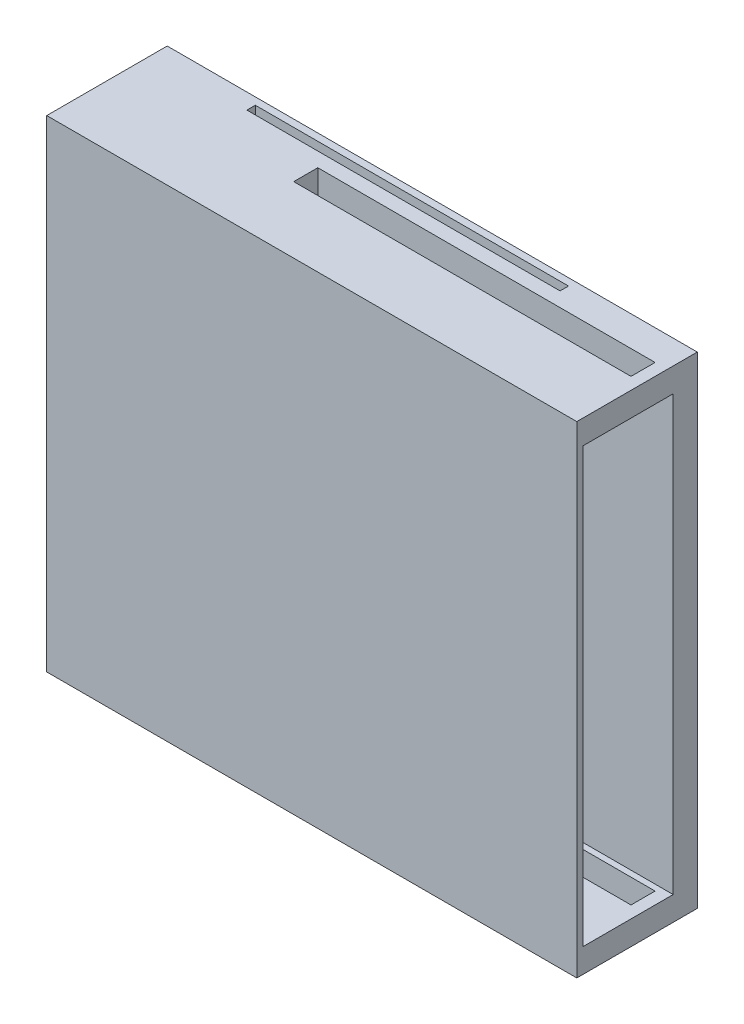
SolidWorks part; units mm, degrees
ref_plane "Front Plane" through (0, 0, 0) normal (0, 0, 1) x (1, 0, 0)
ref_plane "Top Plane" through (0, 0, 0) normal (0, 1, 0) x (1, 0, 0)
ref_plane "Right Plane" through (0, 0, 0) normal (1, 0, 0) x (0, 0, -1)
sketch "Sketch1" plane through (0, 0, 0) normal (0, 1, 0) x (1, 0, 0)
  line L0 (-220, -50) -> (-220, 14.996) construction
  line L1 (-220, 50) -> (220, 50)
  line L2 (-220, 50) -> (-220, -50)
  line L3 (-220, -50) -> (220, -50)
  line L4 (220, 50) -> (220, -50)
  line L5 (-220, 50) -> (220, -50) construction
  line L6 (-220, -50) -> (220, 50) construction
  line L7 (-220, 14.996) -> (70, 14.996) construction
  line L8 (-220, 40.5) -> (-10.877, 40.5) construction
  line L9 (-70, 24.996) -> (210, 24.996)
  line L10 (-70, 24.996) -> (-70, 4.996)
  line L11 (-70, 4.996) -> (210, 4.996)
  line L12 (210, 24.996) -> (210, 4.996)
  line L13 (-70, 24.996) -> (210, 4.996) construction
  line L14 (-70, 4.996) -> (210, 24.996) construction
  line L15 (-10.877, 40.5) -> (-10.877, 50) construction
  line L16 (70, -50) -> (70, 14.996) construction
  line L17 (-140.877, 44) -> (119.123, 44)
  line L18 (-140.877, 44) -> (-140.877, 37)
  line L19 (-140.877, 37) -> (119.123, 37)
  line L20 (119.123, 44) -> (119.123, 37)
  line L21 (-140.877, 44) -> (119.123, 37) construction
  line L22 (-140.877, 37) -> (119.123, 44) construction
  line L23 (119.123, 40.5) -> (220, 40.5) construction
  point P0 (0, 0)
extrude "Boss-Extrude1" add sketch "Sketch1" along normal blind 20
ref_plane "Plane3" through (0, 0, 50) normal (0, 0, 1) x (1, 0, 0)
sketch "Sketch7" plane through (0, 0, 50) normal (0, 0, 1) x (1, 0, 0)
  line L0 (17.6108, 0) -> (17.6108, -380) construction
  line L1 (-220, 0) -> (220, 0) construction
sketch "Sketch8" plane through (0, 0, 0) normal (0, -1, 0) x (1, 0, 0)
  line L0 (-220, 50) -> (-220, 45)
  line L1 (-220, 50) -> (220, 50)
  line L2 (-220, 45) -> (220, 45)
  line L3 (220, 50) -> (220, 45)
  line L4 (-220, -50) -> (-220, 50) construction
extrude "Boss-Extrude2" add sketch "Sketch8" along normal blind 360
pattern_linear "LPattern2" count 2 spacing 380 along (0, -1, 0) of "Boss-Extrude1"
sketch "Sketch10" plane through (0, 0, 0) normal (0, -1, 0) x (1, 0, 0)
  line L0 (220, -50) -> (-220, -50)
  line L1 (220, -50) -> (220, -30)
  line L2 (-220, -50) -> (-220, -30)
  line L3 (220, -30) -> (-220, -30)
extrude "Boss-Extrude3" add sketch "Sketch10" along normal up to surface (360 mm away) up to face at (-55, -360, -2.5)
sketch "Sketch11" plane through (0, 0, -37) normal (0, 0, -1) x (-1, 0, 0)
  line L0 (140.877, 20) -> (140.877, 0) construction
  line L1 (140.877, 20) -> (140.877, 11.5) construction
  line L2 (140.877, 11.5) -> (140.877, 8.5)
  line L3 (140.877, 11.5) -> (-119.1208, 11.5)
  line L4 (140.877, 8.5) -> (-119.1208, 8.5)
  line L5 (-119.1208, 11.5) -> (-119.1208, 8.5)
extrude "Cut-Extrude1" cut sketch "Sketch11" against normal blind 1.5
sketch "Sketch16" plane through (0, 0, -44) normal (0, 0, 1) x (1, 0, 0)
  line L0 (-140.877, 20) -> (-140.877, 11.5) construction
  line L1 (-140.877, 11.5) -> (119.123, 11.5)
  line L2 (119.123, 11.5) -> (119.123, 8.5)
  line L3 (119.123, 8.5) -> (-140.8813, 8.5)
  line L4 (-140.877, 11.5) -> (-140.8813, 8.5)
  dimension "D1" = 90
extrude "Cut-Extrude2" cut sketch "Sketch16" against normal blind 1.5
sketch "Sketch17" plane through (0, 0, -37) normal (0, 0, -1) x (-1, 0, 0)
  line L0 (140.877, -380) -> (140.877, -371.5) construction
  line L1 (140.877, -371.5) -> (140.877, -368.5)
  line L2 (140.877, -371.5) -> (-119.123, -371.5)
  line L3 (140.877, -368.5) -> (-119.123, -368.5)
  line L4 (-119.123, -371.5) -> (-119.123, -368.5)
extrude "Cut-Extrude3" cut sketch "Sketch17" against normal blind 1.5
sketch "Sketch18" plane through (0, 0, -44) normal (0, 0, 1) x (1, 0, 0)
  line L0 (-140.877, -380) -> (-140.877, -371.5) construction
  line L1 (-140.877, -371.5) -> (-140.877, -368.5)
  line L2 (-140.877, -371.5) -> (119.123, -371.5)
  line L3 (-140.877, -368.5) -> (119.123, -368.5)
  line L4 (119.123, -371.5) -> (119.123, -368.5)
extrude "Cut-Extrude4" cut sketch "Sketch18" against normal blind 1.5
